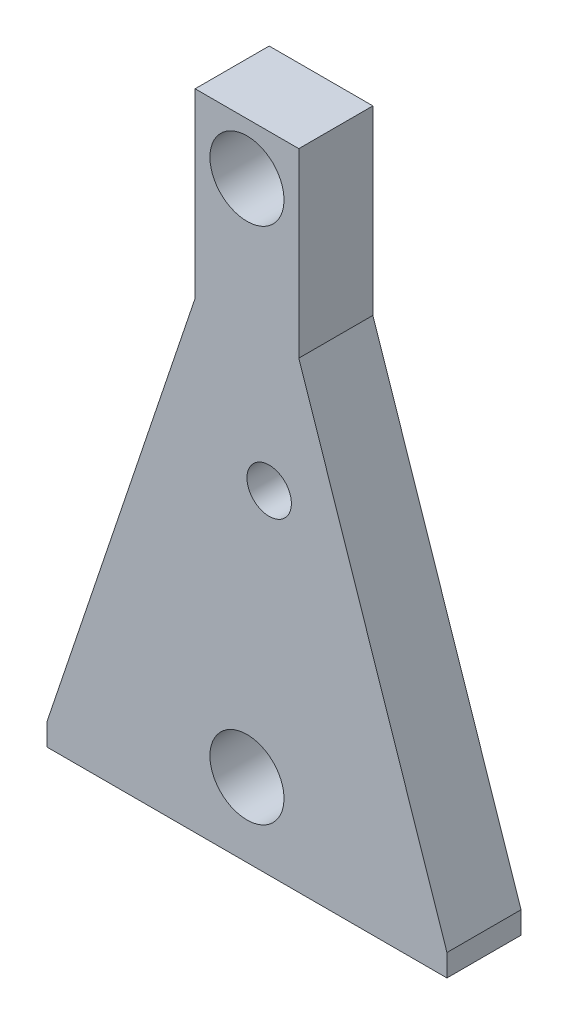
SolidWorks part; units mm, degrees
ref_plane "Plan de face" through (0, 0, 0) normal (0, 0, 1) x (1, 0, 0)
ref_plane "Plan de dessus" through (0, 0, 0) normal (0, 1, 0) x (1, 0, 0)
ref_plane "Plan de droite" through (0, 0, 0) normal (1, 0, 0) x (0, 0, -1)
sketch "Esquisse1" plane through (0, 0, 0) normal (0, 0, 1) x (1, 0, 0)
  line L1 (0, 0) -> (7, 0)
  line L2 (0, 0) -> (0, 42)
  line L3 (0, 42) -> (7, 42)
  line L4 (7, 0) -> (7, 42)
  dimension "D1" = 7
  dimension "D2" = 42
extrude "Boss.-Extru.1" add sketch "Esquisse1" along normal blind 5
sketch "Esquisse2" plane through (0, 0, 0) normal (0, 0, -1) x (-1, 0, 0)
  line L0 (-3.5, 42) -> (-3.5, 0) construction
  line L1 (-7, 42) -> (0, 42) construction
  line L2 (0, 0) -> (-7, 0) construction
  line L3 (-3.5, 38.5) -> (-3.5, 3.5) construction
  circle A0 centre (-3.5, 38.5) radius 2.5
  circle A1 centre (-3.5, 3.5) radius 2.5
  point P11 (-3.5, 21)
  dimension "D1" = 5
  dimension "D2" = 5
  dimension "D3" = 35
extrude "Enlèv. mat.-Extru.1" cut sketch "Esquisse2" against normal through all
sketch "Esquisse3" plane through (0, 0, 0) normal (0, 0, -1) x (-1, 0, 0)
  line L0 (-7, 21) -> (0, 21) construction
  line L1 (-7, 0) -> (-7, 42) construction
  line L2 (0, 42) -> (0, 0) construction
  circle A0 centre (-5, 21) radius 1.5
  dimension "D2" = 3
  dimension "D1" = 2
extrude "Enlèv. mat.-Extru.2" cut sketch "Esquisse3" against normal blind 10
sketch "Esquisse4" plane through (0, 0, 0) normal (0, 0, -1) x (-1, 0, 0)
  line L0 (-7, 29.75) -> (-17, 0)
  line L1 (-7, 0) -> (-7, 42) construction
  line L2 (-17, 0) -> (-7, 0)
  line L3 (-7, 0) -> (-7, 29.75)
  line L4 (-3.5, 38.5) -> (-3.5, 21) construction
  line L5 (-3.5, 29.75) -> (-12.8, 29.75) construction
  line L6 (10, 0) -> (0, 0)
  line L7 (0, 29.75) -> (10, 0)
  line L8 (0, 0) -> (0, 29.75)
  circle A0 centre (-5, 21) radius 1.5 construction
  dimension "D1" = 10
extrude "Boss.-Extru.2" add sketch "Esquisse4" against normal blind 5
sketch "Esquisse7" plane through (0, 0, 0) normal (0, -1, 0) x (-1, 0, 0)
  line L1 (-17, -5) -> (10, -5)
  line L2 (-17, -5) -> (-17, 0)
  line L3 (-17, 0) -> (10, 0)
  line L4 (10, -5) -> (10, 0)
extrude "Boss.-Extru.3" add sketch "Esquisse7" along normal blind 1.49
hole_wizard "Trou taraudé M32" positions "Esquisse8" profile "Esquisse9" tap size "M3" standard "ISO"
sketch "Esquisse8" plane through (0, -1.49, 0) normal (0, -1, 0) x (-1, 0, 0)
  line L0 (4, -2.5) -> (-11, -2.5) construction
  line L2 (-17, -2.5) -> (10, -2.5) construction
  line L3 (-17, 0) -> (-17, -5) construction
  line L4 (10, -5) -> (10, 0) construction
  point P0 (4, -2.5)
  point P2 (-11, -2.5)
  point P16 (-3.5, -2.5)
  dimension "D1" = 15
sketch "Esquisse9" plane through (-4, -1.49, 2.5) normal (1, 0, 0) x (0, 0, -1)
  line L0 (0, 0) -> (0, 9.2511)
  line L1 (0, 9.2511) -> (1.25, 8.5)
  line L2 (1.25, 8.5) -> (1.25, 0)
  line L5 (1.25, 0) -> (0, 0)
  line L10 (0, 9.2511) -> (-1.25, 8.5) construction
  line L11 (0, -6.35) -> (0, 107.95) construction
  dimension "Diamètre du trou pour taraudage" = 2.5
  dimension "Profondeur du trou pour taraudage" = 8.5
  dimension "Angle de pointe" = 118
cosmetic thread "Filetage de perçage3" parameters "D1"=6, "D2"=3
cosmetic thread "Filetage de perçage4" parameters "D1"=6, "D2"=3
